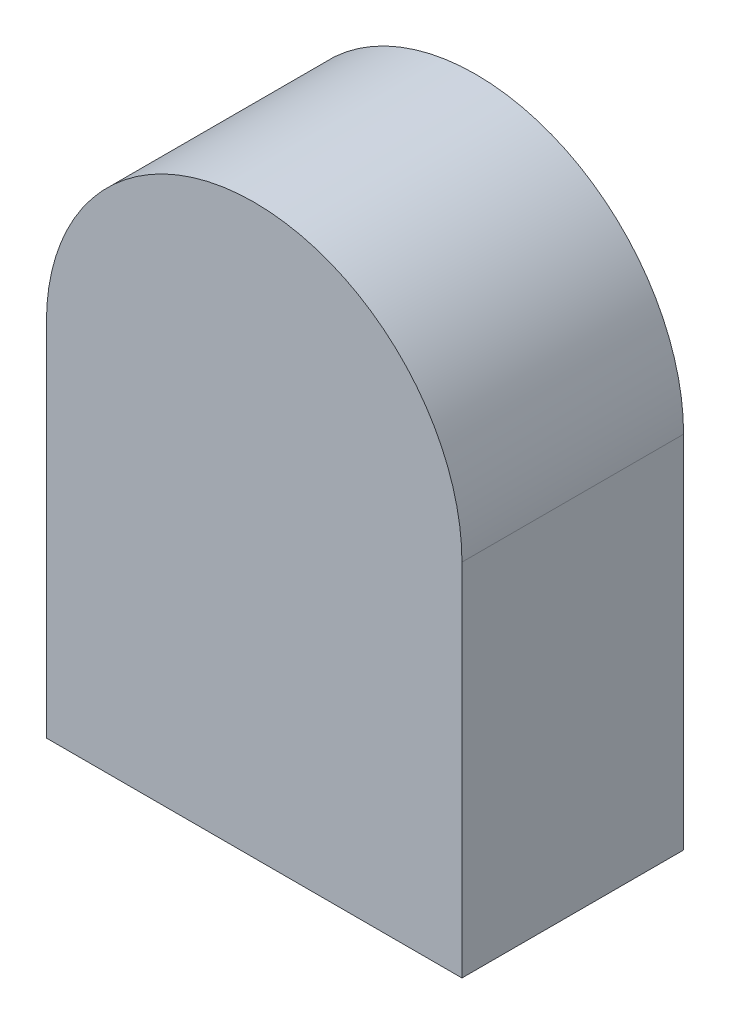
SolidWorks part; units mm, degrees
ref_plane "Front Plane" through (0, 0, 0) normal (0, 0, 1) x (1, 0, 0)
ref_plane "Top Plane" through (0, 0, 0) normal (0, 1, 0) x (1, 0, 0)
ref_plane "Right Plane" through (0, 0, 0) normal (1, 0, 0) x (0, 0, -1)
sketch "Sketch1" plane through (0, 0, 0) normal (0, 0, 1) x (1, 0, 0)
  line L0 (-15, 0) -> (15, 0)
  line L1 (-15, 0) -> (-15, 26)
  line L2 (15, 26) -> (15, 0)
  arc A0 (15, 26) -> (-15, 26) centre (0, 26) ccw
  point P2 (0, 0)
  dimension "D3" = 30
  dimension "D1" = 30
  dimension "D2" = 26
extrude "Extrude-Thin1" add sketch "Sketch1" along normal blind 16 thin thin type one direction reverse wall 1
sketch "Sketch2" plane through (0, 0, 0) normal (0, -1, 0) x (-1, 0, 0)
  line L1 (15, -16) -> (-15, -16) construction
  line L2 (3, -7) -> (3, 0)
  line L3 (15, 0) -> (-15, 0) construction
  line L4 (-3, -7) -> (-3, 0)
  line L5 (-3, 0) -> (3, 0)
  arc A0 (-3, -7) -> (3, -7) centre (0, -7) ccw
  dimension "D1" = 6
  dimension "D2" = 9
extrude "Cut-Extrude1" cut sketch "Sketch2" against normal blind 10
sketch "Sketch3" plane through (0, 0, 16) normal (0, 0, 1) x (1, 0, 0)
  line L0 (-15, 0) -> (15, 0) construction
  line L1 (15, 0) -> (15, 26) construction
  line L2 (-15, 26) -> (-15, 0) construction
  line L3 (-15, 0) -> (15, 0)
  line L4 (15, 0) -> (15, 26)
  line L5 (-15, 26) -> (-15, 0)
  arc A0 (15, 26) -> (-15, 26) centre (0, 26) ccw construction
  arc A1 (15, 26) -> (-15, 26) centre (0, 26) ccw
extrude "Boss-Extrude1" add sketch "Sketch3" against normal blind 1.5
